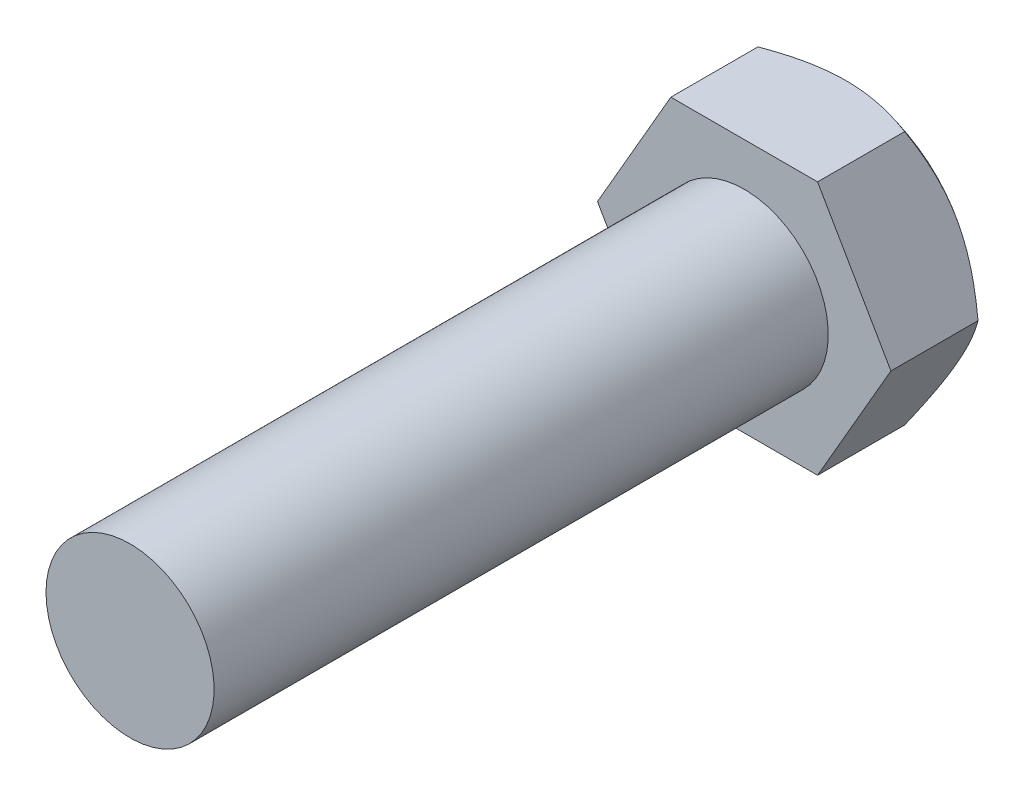
SolidWorks part; units mm, degrees
ref_plane "Alzado" through (0, 0, 0) normal (0, 0, 1) x (1, 0, 0)
ref_plane "Planta" through (0, 0, 0) normal (0, 1, 0) x (1, 0, 0)
ref_plane "Vista lateral" through (0, 0, 0) normal (1, 0, 0) x (0, 0, -1)
sketch "Croquis1" plane through (0, 0, 0) normal (0, 0, 1) x (1, 0, 0)
  line L1 (13.8564, 0) -> (6.9282, 12)
  line L2 (6.9282, 12) -> (-6.9282, 12)
  line L3 (-6.9282, 12) -> (-13.8564, 0)
  line L4 (-13.8564, 0) -> (-6.9282, -12)
  line L5 (-6.9282, -12) -> (6.9282, -12)
  line L6 (6.9282, -12) -> (13.8564, 0)
  circle A0 centre (0, 0) radius 12 construction
  dimension "D1" = 24
extrude "Saliente-Extruir1" add sketch "Croquis1" along normal blind 10
sketch "Croquis2" plane through (0, 0, 10) normal (0, 0, 1) x (1, 0, 0)
  circle A0 centre (0, 0) radius 7.9375
  dimension "D1" = 15.875
extrude "Saliente-Extruir2" add sketch "Croquis2" along normal blind 58
sketch "Croquis3" plane through (0, 0, 0) normal (0, 0, -1) x (-1, 0, 0)
  circle A0 centre (0, 0) radius 11.5
  circle A1 centre (0, 0) radius 28.2141
  dimension "D1" = 23
extrude "Cortar-Extruir1" cut sketch "Croquis3" against normal blind 50.8 draft 53
